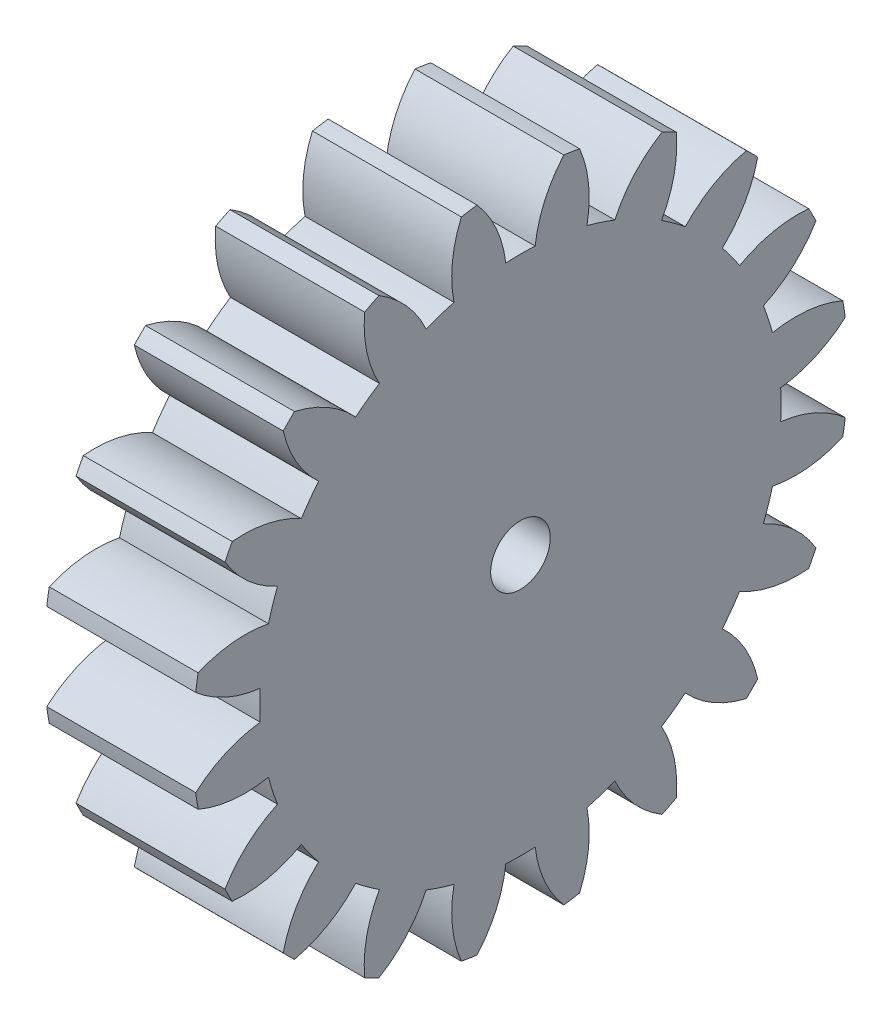
SolidWorks part; units mm, degrees
ref_plane "Plane1" through (0, 0, 0) normal (0, 0, 1) x (1, 0, 0)
ref_plane "Plane2" through (0, 0, 0) normal (0, 1, 0) x (1, 0, 0)
ref_plane "Plane3" through (0, 0, 0) normal (1, 0, 0) x (0, 0, -1)
sketch "HoldingSke" plane through (0, 0, 0) normal (0, 1, 0) x (1, 0, 0)
  line L0 (0, 0) -> (0.4698, -0.171)
  line L1 (-15, 0) -> (100, 0) construction
  line L2 (0, 0) -> (-2.1039, 2.3779)
  line L3 (0, 0) -> (-11.863, 4.5341)
  line L4 (0, 0) -> (8.1152, 2.9537)
  line L5 (0, 0) -> (-46.8476, -17.4728)
  line L6 (0, 0) -> (-8.2896, -5.593)
  line L7 (-2.1039, 2.3779) -> (8.6586, 51.2059)
  line L8 (-76.2, 54.61) -> (-76.1, 54.61)
  line L9 (-71.009, 38.7566) -> (-53.1078, 45.2721)
  line L10 (-76.2, 71.12) -> (104.1128, 71.12)
  line L11 (0, 0) -> (-10, 0)
  line L12 (-76.2, 101.6) -> (-76.133, 101.6)
  line L13 (24.9733, 27.94) -> (52.9518, 28.4284)
  line L14 (24.9733, 27.94) -> (24.9743, 27.94)
  line L15 (24.9733, 27.94) -> (100.4006, 29.5858)
  line L16 (-63.627, -2) -> (-12.827, -2)
  circle A0 centre (0, 0) radius 0.4
  circle A1 centre (0, 0) radius 17.499
  circle A2 centre (0, 0) radius 37.5
  circle A3 centre (0, 0) radius 0.4
  dimension "MHD" = 34.998
  dimension "Hub_dia" = 75
  dimension "Bore" = 0.8
  dimension "MBD" = 0.8
  dimension "Num_teeth" = 20
  dimension "Pitch" = 0.5
  dimension "Overall_len" = 50
  dimension "Show_teeth" = 20
  dimension "Thickness" = 10
  dimension "OAL" = 50.0001
  dimension "T_dim" = 0.1
  dimension "Ap" = 20
  dimension "H" = 19.05
  dimension "Pitch_radius" = 180.3128
  dimension "Width" = 10
  dimension "Backlash" = 0.067
  dimension "Addendum_fac" = 1
  dimension "Dedendum_fac" = 1.25
  dimension "Clearance_fac" = 0.25
  dimension "Dedendum_add" = 0.001
  dimension "Module" = 2
sketch "BasProSke" plane through (0, 0, 0) normal (0, 1, 0) x (1, 0, 0)
  line L0 (-10, 0) -> (60, 0) construction
  line L1 (0, 0) -> (0, 22)
  line L2 (0, 0) -> (10, 0)
  line L3 (10, 0) -> (10, 22)
  line L4 (10, 22) -> (0, 22)
  dimension "Thickness" = 10
  dimension "Diameter" = 44
revolve "Base-Revolve" add sketch "BasProSke" angle 360 about L0
sketch "TooCutSke" plane through (0, 0, 0) normal (1, 0, 0) x (0, 0, -1)
  line L1 (0, 0) -> (0, 107) construction
  line L2 (0, 0) -> (-1.6864, 19.9288) construction
  line L3 (0, 0) -> (-6.2409, 39.4033) construction
  line L4 (-1.6864, 19.9288) -> (-3.1204, 19.7016) construction
  arc A0 (0.9862, 17.4712) -> (-0.9862, 17.4712) centre (0, 0) ccw
  arc A1 (2.9329, 21.8293) -> (-2.9329, 21.8293) centre (0, 0) ccw
  circle A2 centre (0, 0) radius 20 construction
  circle A3 centre (0, 0) radius 18.7939 construction
  arc A4 (-0.9862, 17.4712) -> (-2.9329, 21.8293) centre (-8.9313, 16.536) ccw
  arc A5 (2.9329, 21.8293) -> (0.9862, 17.4712) centre (8.9313, 16.536) ccw
  dimension "Root_dia" = 34.998
  dimension "Overcut_dia" = 44.0508
  dimension "Pitch_dia" = 40
  dimension "Base_dia" = 37.5877
  dimension "Flank_rad" = 8
  dimension "Half_ang" = 9
  dimension "Half_CT" = 1.4519
extrude "ToothCut" cut sketch "TooCutSke" along normal through all
fillet "Breaks" [suppressed] radius 0.04
fillet "RootFillets" [suppressed] radius 0.501
pattern_circular "TeethCuts" count 20 every 18 about axis through (-10, 0, 0) along (1, 0, 0) of "ToothCut", "RootFillets", "Breaks"
sketch "HubNeaOneSke" plane through (0, 0, 0) normal (-1, 0, 0) x (0, 0, 1)
  circle A0 centre (0, 0) radius 17.499
  dimension "Diameter" = 34.998
extrude "HubNearOne" [suppressed] add sketch "HubNeaOneSke" along normal blind 40.0001
sketch "HubNeaBotSke" plane through (0, 0, 0) normal (-1, 0, 0) x (0, 0, 1)
  circle A0 centre (0, 0) radius 17.499
  dimension "Diameter" = 34.998
extrude "HubNearBoth" [suppressed] add sketch "HubNeaBotSke" along normal blind 20
ref_plane "FarPln" through (10, 0, 0) normal (1, 0, 0) x (0, 0, -1)
sketch "HubFarSke" plane through (10, 0, 0) normal (1, 0, 0) x (0, 0, -1)
  circle A0 centre (0, 0) radius 17.499
  dimension "Diameter" = 34.998
extrude "HubFar" [suppressed] add sketch "HubFarSke" along normal blind 20
sketch "BorSke" plane through (0, 0, 0) normal (1, 0, 0) x (0, 0, -1)
  circle A0 centre (0, 0) radius 0.4
  dimension "Diameter" = 0.8
extrude "Bore" cut sketch "BorSke" along normal mid plane 100.0001
sketch "KeySke" plane through (0, 0, 0) normal (1, 0, 0) x (0, 0, -1)
  line L0 (-0.05, 0) -> (-0.05, 0.5)
  line L1 (-0.05, 0.5) -> (0.05, 0.5)
  line L2 (0.05, 0.5) -> (0.05, 0)
  line L3 (0, 0) -> (0, 34) construction
  line L4 (-0.05, 0) -> (0.05, 0)
  dimension "Offset" = 0.5
  dimension "Width" = 0.1
extrude "Keyway" [suppressed] cut sketch "KeySke" along normal mid plane 100.0001
pattern_circular "Keyway2" [suppressed] count 2 every 90 about axis through (-10, 0, 0) along (1, 0, 0)
sketch "Sketch1" plane through (0, 0, 0) normal (-1, 0, 0) x (0, 0, 1)
  line L12 (-5.9472, -3.5539) -> (0.1042, -6.9274)
  line L13 (0.1042, -6.9274) -> (6.0514, -3.3735)
  line L14 (6.0514, -3.3735) -> (5.9472, 3.5539)
  line L15 (5.9472, 3.5539) -> (-0.1042, 6.9274)
  line L16 (-0.1042, 6.9274) -> (-6.0514, 3.3735)
  line L17 (-6.0514, 3.3735) -> (-5.9472, -3.5539)
extrude "Cut-Extrude1" cut sketch "Sketch1" against normal blind 6
sketch "Sketch2" plane through (10, 0, 0) normal (1, 0, 0) x (0, 0, -1)
  circle A1 centre (0, 0) radius 2
extrude "Cut-Extrude2" cut sketch "Sketch2" against normal blind 6
sketch "Sketch4" plane through (0, 0, 0) normal (-1, 0, 0) x (0, 0, 1)
  line L12 (-6.3465, 3.5185) -> (-6.2378, -3.7149)
  line L13 (-6.2378, -3.7149) -> (0.0713, -7.2321)
  line L14 (0.0713, -7.2321) -> (6.3341, -3.4896)
  line L15 (6.3341, -3.4896) -> (6.2255, 3.7319)
  line L16 (6.2255, 3.7319) -> (-0.094, 7.2549)
  line L17 (-0.094, 7.2549) -> (-6.3465, 3.5185)
extrude "Cut-Extrude3" cut sketch "Sketch4" against normal blind 6
equation "' \"Module@HoldingSke\" = 6.35"
equation "' \"Num_teeth@HoldingSke\" = 12"
equation "' \"Ap@HoldingSke\" =  20"
equation "' \"Ap@HoldingSke\" = 20"
equation "' \"Width@HoldingSke\" = 0.5 * 25.4"
equation "' \"Hub_dia@HoldingSke\"= 1 * 25.4"
equation "' \"Hub_dia@HoldingSke\" = 1 * 25.4"
equation "' \"Overall_len@HoldingSke\" = 1.0 * 25.4"
equation "' \"Bore@HoldingSke\" = 0.75 * 25.4"
equation "' \"T_dim@HoldingSke\" = 0.1 * 25.4"
equation "' \"Width@KeySke\" = 0.25 * 25.4"
equation "' \"Show_teeth@HoldingSke\" = 13"
equation "' \"Backlash@HoldingSke\" = 0.009 * 25.4"
equation "' \"Addendum_fac@HoldingSke\" = 1.0"
equation "' \"Dedendum_fac@HoldingSke\" = 1.25"
equation "' \"Dedendum_add@HoldingSke\" = 0.00005 * 25.4"
equation "' \"Clearance_fac@HoldingSke\" = 0.25"
equation "\"Pitch@HoldingSke\" = 1 / \"Module@HoldingSke\""
equation "\"Overcut_dia@TooCutSke\" = (\"Num_teeth@HoldingSke\" + 2 * \"Addendum_fac@HoldingSke\") / \"Pitch@HoldingSke\" + 0.002 * 25.4"
equation "\"Pitch_dia@TooCutSke\" = \"Num_teeth@HoldingSke\" / \"Pitch@HoldingSke\""
equation "\"Base_dia@TooCutSke\" = \"Num_teeth@HoldingSke\" / \"Pitch@HoldingSke\" * cos((\"Ap@HoldingSke\"  * 3.14159265 / 180))"
equation "\"Root_dia@TooCutSke\" = (\"Num_teeth@HoldingSke\" + 2) / \"Pitch@HoldingSke\" - 2 * (\"Addendum_fac@HoldingSke\" + \"Dedendum_fac@HoldingSke\") / \"Pitch@HoldingSke\" - \"Dedendum_add@HoldingSke\" * 2"
equation "\"Half_ang@TooCutSke\" = 180 / \"Num_teeth@HoldingSke\""
equation "\"Half_CT@TooCutSke\" = \"Num_teeth@HoldingSke\" / \"Pitch@HoldingSke\" * sin((3.14159265 / 2 / \"Num_teeth@HoldingSke\")) / 2 - 7 * \"Backlash@HoldingSke\" / 4"
equation "\"Flank_rad@TooCutSke\" = \"Num_teeth@HoldingSke\" / \"Pitch@HoldingSke\" / 5"
equation "\"Radius@RootFillets\" = \"Clearance_fac@HoldingSke\" / \"Pitch@HoldingSke\" + \"Dedendum_add@HoldingSke\""
equation "\"Break_rad@Breaks\" = 0.02 / \"Pitch@HoldingSke\""
equation "\"Thickness@HoldingSke\" = \"Width@HoldingSke\""
equation "\"OAL@HoldingSke\" = \"Thickness@HoldingSke\""
equation "\"MHD@HoldingSke\" = (\"Num_teeth@HoldingSke\" + 2) / \"Pitch@HoldingSke\" - 2 * (\"Addendum_fac@HoldingSke\" + \"Dedendum_fac@HoldingSke\")  / \"Pitch@HoldingSke\" - \"Dedendum_add@HoldingSke\" * 2"
equation "\"MBD@HoldingSke\" = (\"Num_teeth@HoldingSke\" + 2) / \"Pitch@HoldingSke\" - 2 * (\"Addendum_fac@HoldingSke\" + \"Dedendum_fac@HoldingSke\")  / \"Pitch@HoldingSke\" - \"Dedendum_add@HoldingSke\" * 2 - 0.002 * 25.4"
equation "\"MHD@HoldingSke\" = ((sgn( \"MHD@HoldingSke\" - \"Hub_dia@HoldingSke\" )-1)*( \"MHD@HoldingSke\" - \"Hub_dia@HoldingSke\" ))/-2+ \"Hub_dia@HoldingSke\""
equation "\"MBD@HoldingSke\" = ((sgn( \"MBD@HoldingSke\" - \"Bore@HoldingSke\" )-1)*( \"MBD@HoldingSke\" - \"Bore@HoldingSke\" ))/-2+ \"Bore@HoldingSke\""
equation "\"OAL@HoldingSke\" = ((sgn( \"OAL@HoldingSke\" - \"Overall_len@HoldingSke\" )+1)*( \"OAL@HoldingSke\" - \"Overall_len@HoldingSke\" ))/2 + \"Overall_len@HoldingSke\" + 0.000002 * 25.4"
equation "\"Num_teeth@TeethCuts\" = int( \"Show_teeth@HoldingSke\" ) + 1"
equation "\"Num_teeth@TeethCuts\" = ((sgn( \"Num_teeth@TeethCuts\" - \"Num_teeth@HoldingSke\" )-1)*( \"Num_teeth@TeethCuts\" - \"Num_teeth@HoldingSke\" ))/-2+ \"Num_teeth@HoldingSke\""
equation "\"Num_teeth@TeethCuts\" = ((sgn( \"Num_teeth@TeethCuts\" - 2.0)+1)*( \"Num_teeth@TeethCuts\" - 2.0))/2 +2.0"
equation "\"Angle@TeethCuts\" = 360.0 / \"Num_teeth@HoldingSke\""
equation "\"Diameter@BasProSke\" = (\"Num_teeth@HoldingSke\" + 2 * \"Addendum_fac@HoldingSke\") / \"Pitch@HoldingSke\""
equation "\"Thickness@BasProSke\"  = \"Thickness@HoldingSke\""
equation "' \"Fillet_rad@BasProSke\" =  \"Thickness@HoldingSke\" * 0.05"
equation "' \"Fillet_rad@BasProSke\" = \"Thickness@HoldingSke\" * 0.05"
equation "\"MHD@HoldingSke\" = ((sgn( \"MHD@HoldingSke\" - \"Root_dia@TooCutSke\" )-1)*( \"MHD@HoldingSke\" - \"Root_dia@TooCutSke\" ))/-2+ \"Root_dia@TooCutSke\""
equation "\"Diameter@HubNeaOneSke\" = \"MHD@HoldingSke\""
equation "\"Length@HubNearOne\" = \"OAL@HoldingSke\" - \"Thickness@BasProSke\""
equation "\"Diameter@HubNeaBotSke\" = \"MHD@HoldingSke\""
equation "\"Length@HubNearBoth\" = ( \"OAL@HoldingSke\" - \"Thickness@BasProSke\" ) / 2.0"
equation "\"Thickness@FarPln\" = \"Thickness@BasProSke\""
equation "\"Diameter@HubFarSke\" = \"MHD@HoldingSke\""
equation "\"Length@HubFar\" = ( \"OAL@HoldingSke\" - \"Thickness@BasProSke\" ) / 2.0"
equation "\"Diameter@BorSke\" = \"MBD@HoldingSke\""
equation "\"D1@Bore\" = \"OAL@HoldingSke\" * 2.0"
equation "\"D1@Keyway\" = \"OAL@HoldingSke\" * 2.0"
equation "\"Offset@KeySke\" = \"T_dim@HoldingSke\" + \"MBD@HoldingSke\" / 2.0"
